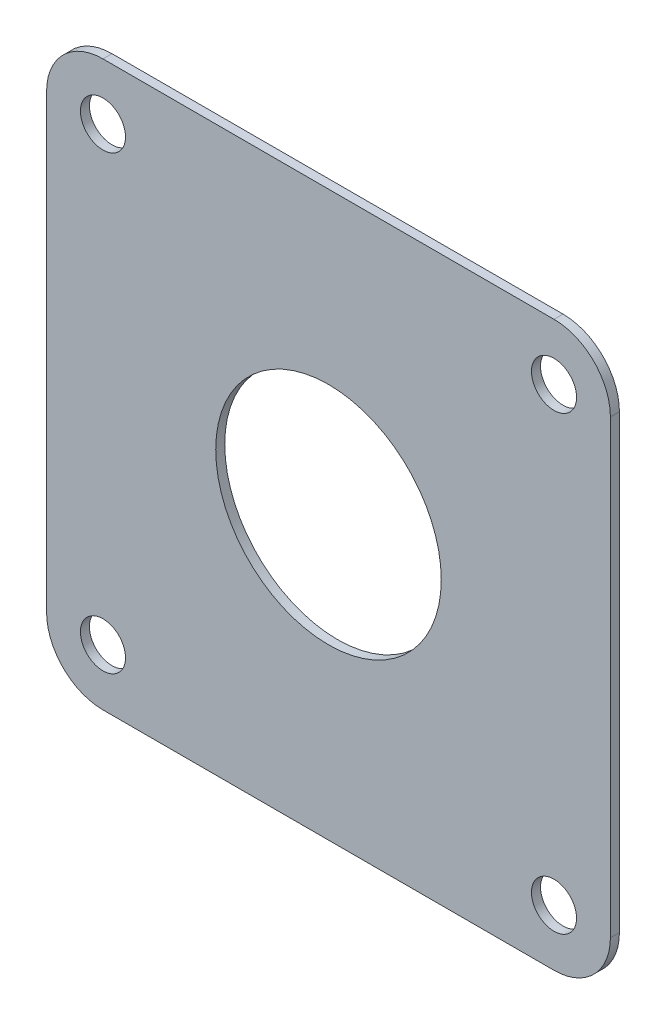
SolidWorks part; units mm, degrees
material "mach_pin"
ref_plane "Front Plane" through (0, 0, 0) normal (0, 0, 1) x (1, 0, 0)
ref_plane "Top Plane" through (0, 0, 0) normal (0, 1, 0) x (1, 0, 0)
ref_plane "Right Plane" through (0, 0, 0) normal (1, 0, 0) x (0, 0, -1)
sketch "Sketch1" plane through (0, 0, 0) normal (0, 0, 1) x (1, 0, 0)
  line L1 (-25, 25) -> (25, 25)
  line L2 (-25, 25) -> (-25, -25)
  line L3 (-25, -25) -> (25, -25)
  line L4 (25, 25) -> (25, -25)
  line L5 (-25, 25) -> (25, -25) construction
  line L6 (-25, -25) -> (25, 25) construction
  point P0 (0, 0)
  dimension "D1" = 50
  dimension "D2" = 50
extrude "Boss-Extrude1" add sketch "Sketch1" along normal blind 0.8
fillet "Fillet1" radius 5 4 edges at (-25, -25, 0.4) (25, -25, 0.4) (25, 25, 0.4) (-25, 25, 0.4)
sketch "Sketch2" plane through (0, 0, 0) normal (0, 0, -1) x (-1, 0, 0)
  circle A0 centre (-20, 20) radius 2
  circle A1 centre (20, 20) radius 2
  circle A2 centre (20, -20) radius 2
  circle A3 centre (-20, -20) radius 2
  dimension "D1" = 4
  dimension "D2" = 4
  dimension "D3" = 4
  dimension "D4" = 4
  dimension "D5" = 20
  dimension "D6" = 20
  dimension "D7" = 20
  dimension "D8" = 20
  dimension "D9" = 20
  dimension "D10" = 20
  dimension "D11" = 20
  dimension "D12" = 20
extrude "Cut-Extrude1" cut sketch "Sketch2" against normal through all
sketch "Sketch3" plane through (0, 0, 0) normal (0, 0, -1) x (-1, 0, 0)
  circle A0 centre (0, 0) radius 19.8072
extrude "Boss-Extrude2" add sketch "Sketch3" along normal blind 1.5
sketch "Sketch4" plane through (0, 0, -1.5) normal (0, 0, -1) x (-1, 0, 0)
  circle A0 centre (0, 0) radius 17.5
  dimension "D1" = 35
extrude "Cut-Extrude2" cut sketch "Sketch4" against normal blind 1.5
sketch "Sketch6" plane through (0, 0, 0) normal (0, 0, -1) x (-1, 0, 0)
  circle A0 centre (0, 0) radius 10
  dimension "D1" = 20
extrude "Cut-Extrude3" cut sketch "Sketch6" against normal through all
